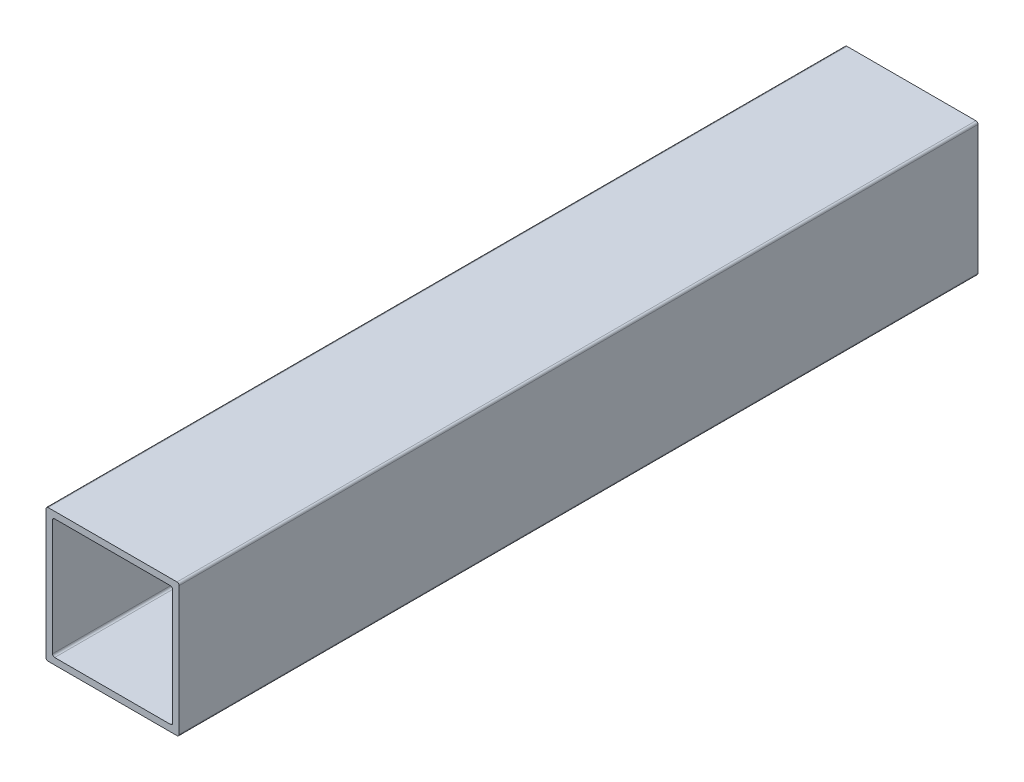
SolidWorks part; units mm, degrees
ref_plane "Front Plane" through (0, 0, 0) normal (0, 0, 1) x (1, 0, 0)
ref_plane "Top Plane" through (0, 0, 0) normal (0, 1, 0) x (1, 0, 0)
ref_plane "Right Plane" through (0, 0, 0) normal (1, 0, 0) x (0, 0, -1)
sketch "Sketch1" plane through (0, 0, 0) normal (0, 0, 1) x (1, 0, 0)
  line L1 (0, 0) -> (25.4, 0)
  line L2 (0, 0) -> (0, 25.4)
  line L3 (0, 25.4) -> (25.4, 25.4)
  line L4 (25.4, 0) -> (25.4, 25.4)
  line L5 (1.2446, 1.2446) -> (24.1554, 1.2446)
  line L6 (1.2446, 1.2446) -> (1.2446, 24.1554)
  line L7 (1.2446, 24.1554) -> (24.1554, 24.1554)
  line L8 (24.1554, 1.2446) -> (24.1554, 24.1554)
  dimension "D1" = 1.2446
  dimension "D2" = 1.2446
  dimension "D3" = 25.4
  dimension "D4" = 1.2446
extrude "Boss-Extrude1" add sketch "Sketch1" against normal blind 152.4
fillet "Fillet1" radius 0.4064 4 edges at (0, 0, -76.2) (25.4, 0, -76.2) (0, 25.4, -76.2) (25.4, 25.4, -76.2)
fillet "Fillet2" radius 0.4064 4 edges at (1.2446, 24.1554, -76.2) (24.1554, 24.1554, -76.2) (24.1554, 1.2446, -76.2) (1.2446, 1.2446, -76.2)
